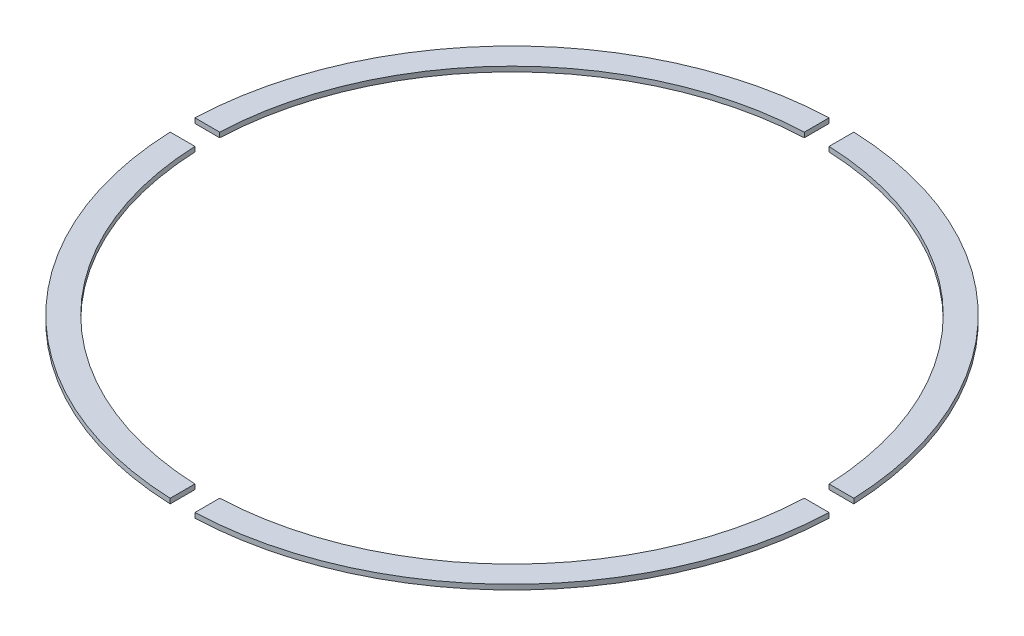
SolidWorks part; units mm, degrees
ref_plane "Front Plane" through (0, 0, 0) normal (0, 0, 1) x (1, 0, 0)
ref_plane "Top Plane" through (0, 0, 0) normal (0, 1, 0) x (1, 0, 0)
ref_plane "Right Plane" through (0, 0, 0) normal (1, 0, 0) x (0, 0, -1)
sketch "Sketch1" plane through (0, 0, 0) normal (0, 1, 0) x (1, 0, 0)
  line L0 (185, 0) -> (-185, 0) construction
  circle A0 centre (0, 0) radius 185
  circle A1 centre (0, 0) radius 200
  dimension "D1" = 370
  dimension "D2" = 400
extrude "Boss-Extrude1" add sketch "Sketch1" along normal mid plane 3
sketch "Sketch2" plane through (0, 0, 0) normal (0, 1, 0) x (1, 0, 0)
  line L1 (157.6447, 7.5) -> (227.3553, 7.5)
  line L2 (157.6447, 7.5) -> (157.6447, -7.5)
  line L3 (157.6447, -7.5) -> (227.3553, -7.5)
  line L4 (227.3553, 7.5) -> (227.3553, -7.5)
  line L5 (157.6447, 7.5) -> (227.3553, -7.5) construction
  line L6 (157.6447, -7.5) -> (227.3553, 7.5) construction
  circle A0 centre (0, 0) radius 192.5 construction
  circle A1 centre (0, 0) radius 185 construction
  point P5 (192.5, 0)
  dimension "D1" = 7.5
  dimension "D2" = 15
extrude "Cut-Extrude1" cut sketch "Sketch2" against normal through all and the other way through all
sketch "Sketch4" plane through (0, 0, 0) normal (1, 0, 0) x (0, 0, -1)
  line L0 (0, 167.5) -> (0, -167.5) construction
  dimension "D1" = 335
pattern_circular "CirPattern1" count 4 every 90 about axis through (0, 0, 0) along (0, 1, 0) of "Cut-Extrude1"
sketch "Sketch5" plane through (0, 0, 0) normal (0, 1, 0) x (1, 0, 0)
  line L0 (0, 250) -> (0, -250) construction
  dimension "D1" = 500
